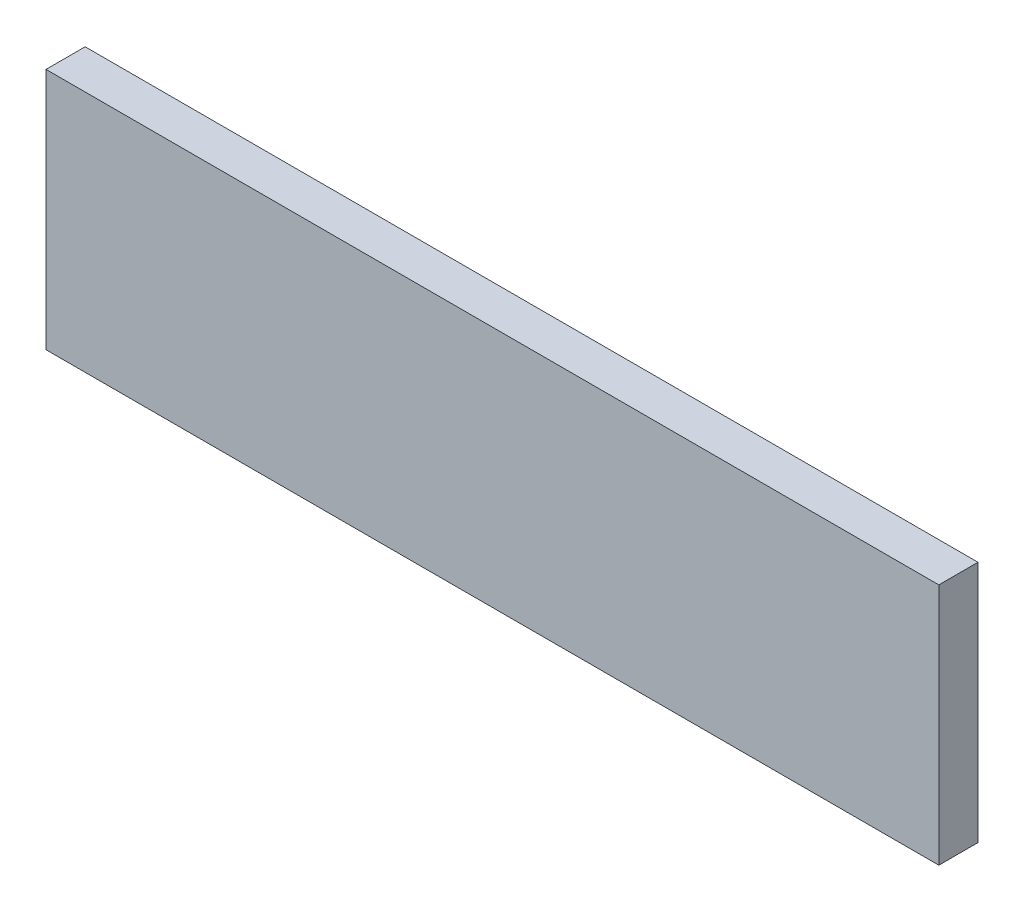
SolidWorks part; units mm, degrees
ref_plane "Front Plane" through (0, 0, 0) normal (0, 0, 1) x (1, 0, 0)
ref_plane "Top Plane" through (0, 0, 0) normal (0, 1, 0) x (1, 0, 0)
ref_plane "Right Plane" through (0, 0, 0) normal (1, 0, 0) x (0, 0, -1)
sketch "Sketch1" plane through (0, 0, 0) normal (0, 0, 1) x (1, 0, 0)
  line L1 (0, 0) -> (228, 0)
  line L2 (0, 0) -> (0, 62)
  line L3 (0, 62) -> (228, 62)
  line L4 (228, 0) -> (228, 62)
  dimension "D1" = 62
  dimension "D2" = 228
extrude "Boss-Extrude1" add sketch "Sketch1" along normal blind 10
